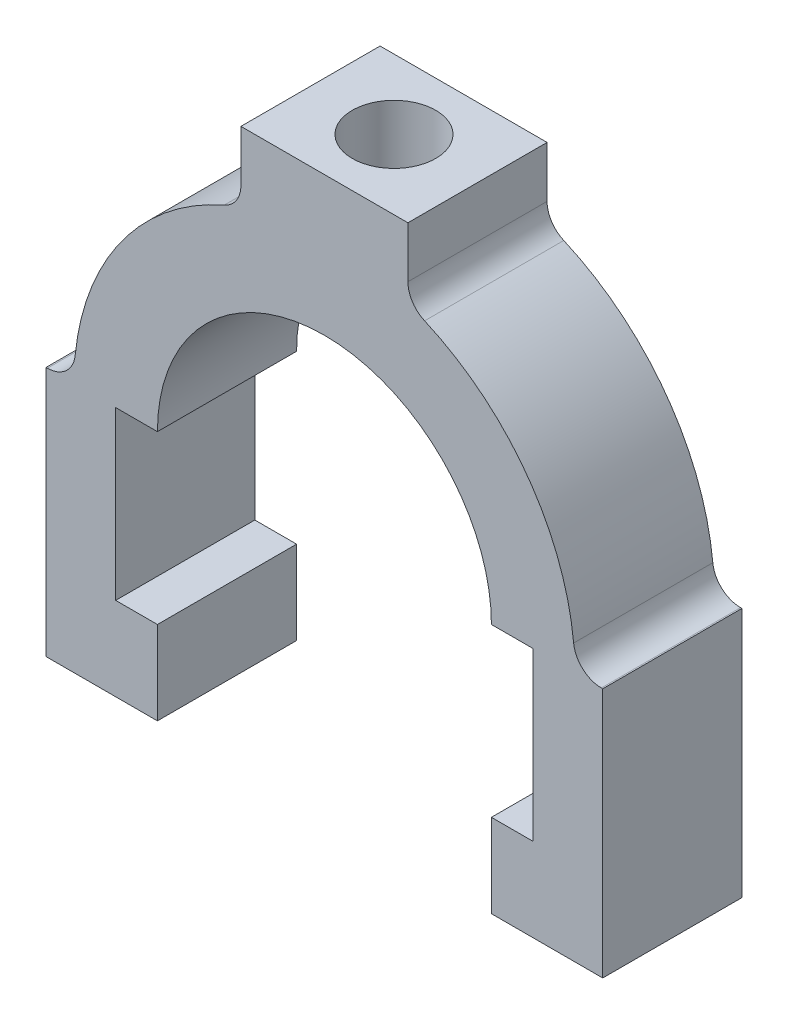
SolidWorks part; units mm, degrees
ref_plane "Front Plane" through (0, 0, 0) normal (0, 0, 1) x (1, 0, 0)
ref_plane "Top Plane" through (0, 0, 0) normal (0, 1, 0) x (1, 0, 0)
ref_plane "Right Plane" through (0, 0, 0) normal (1, 0, 0) x (0, 0, -1)
sketch "Sketch1" plane through (0, 0, 0) normal (0, 0, 1) x (1, 0, 0)
  line L0 (-24, 0) -> (-30, 0) construction
  line L1 (24, 0) -> (30, 0) construction
  line L2 (36, 0) -> (40, 0) construction
  line L3 (-36, 0) -> (-40, 0) construction
  line L4 (24, 0) -> (30, 0)
  line L5 (30, 0) -> (30, -24)
  line L6 (30, -24) -> (24, -24)
  line L7 (24, -24) -> (24, -36)
  line L8 (24, -36) -> (40, -36)
  line L9 (40, -36) -> (40, 0)
  line L10 (40, 0) -> (39.7995, 0)
  line L11 (-40, -36) -> (-40, 0)
  line L12 (-40, 0) -> (-39.7995, 0)
  line L13 (-24, 0) -> (-30, 0)
  line L14 (-30, 0) -> (-30, -24)
  line L15 (-24, -36) -> (-40, -36)
  line L16 (-24, -24) -> (-24, -36)
  line L17 (-30, -24) -> (-24, -24)
  line L20 (-12, 36.6606) -> (-12, 44)
  line L21 (-12, 44) -> (12, 44)
  line L22 (12, 36.6606) -> (12, 44)
  arc A0 (24, 0) -> (-24, 0) centre (0, 0) ccw
  arc A1 (35.8195, 3.6) -> (14.4, 32.9945) centre (0, 0) ccw
  arc A2 (-14.4, 32.9945) -> (-35.8195, 3.6) centre (0, 0) ccw
  arc A3 (-14.4, 32.9945) -> (-12, 36.6606) centre (-16, 36.6606) ccw
  arc A4 (14.4, 32.9945) -> (12, 36.6606) centre (16, 36.6606) cw
  arc A5 (39.7995, 0) -> (35.8195, 3.6) centre (39.7995, 4) cw
  arc A6 (-39.7995, 0) -> (-35.8195, 3.6) centre (-39.7995, 4) ccw
  point P5 (-12, 33.9411)
  point P22 (-30, -12)
  dimension "D1" = 72
  dimension "D2" = 48
  dimension "D10" = 4
  dimension "D11" = 4
  dimension "D12" = 4
  dimension "D13" = 4
  dimension "D3" = 16
  dimension "D4" = 80
  dimension "D5" = 10
  dimension "D6" = 12
  dimension "D7" = 36
  dimension "D8" = 24
  dimension "D9" = 80
extrude "Boss-Extrude1" add sketch "Sketch1" along normal blind 20
sketch "Sketch2" plane through (0, 44, 0) normal (0, 1, 0) x (1, 0, 0)
  circle A0 centre (0, -10) radius 6
  dimension "D1" = 12
extrude "Cut-Extrude1" cut sketch "Sketch2" against normal blind 25
